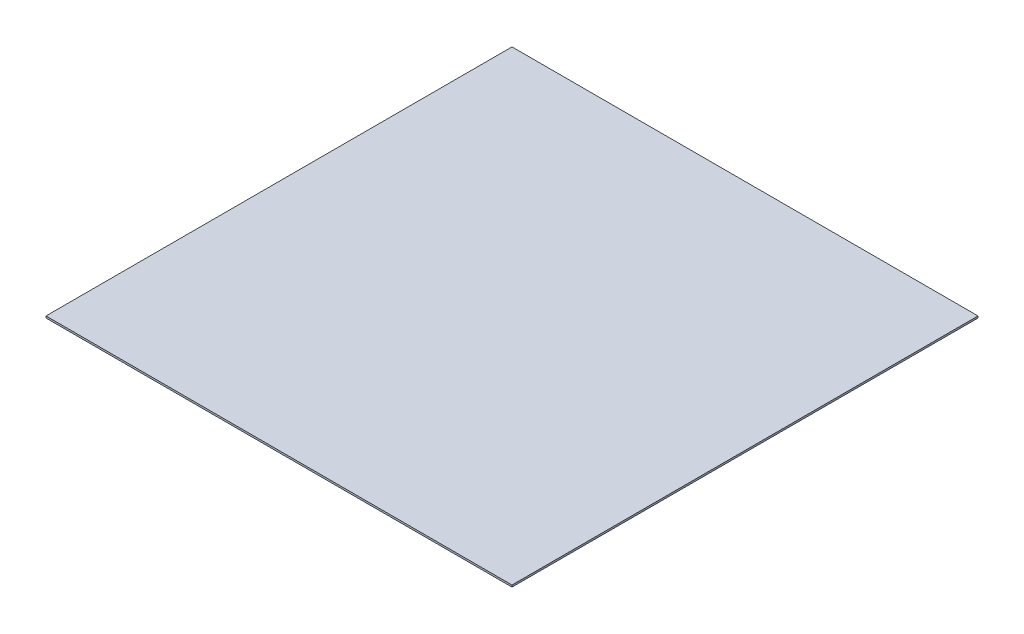
SolidWorks part; units mm, degrees
material "AISI 1045 Steel, cold drawn"
ref_plane "Front Plane" through (0, 0, 0) normal (0, 0, 1) x (1, 0, 0)
ref_plane "Top Plane" through (0, 0, 0) normal (0, 1, 0) x (1, 0, 0)
ref_plane "Right Plane" through (0, 0, 0) normal (1, 0, 0) x (0, 0, -1)
sketch "Sketch1" plane through (0, 0, 0) normal (0, 1, 0) x (1, 0, 0)
  line L1 (252, -252) -> (-252, -252)
  line L2 (252, -252) -> (252, 252)
  line L3 (252, 252) -> (-252, 252)
  line L4 (-252, -252) -> (-252, 252)
  line L5 (252, -252) -> (-252, 252) construction
  line L6 (252, 252) -> (-252, -252) construction
  point P0 (0, 0)
  dimension "D1" = 504
extrude "Boss-Extrude1" add sketch "Sketch1" along normal mid plane 2
